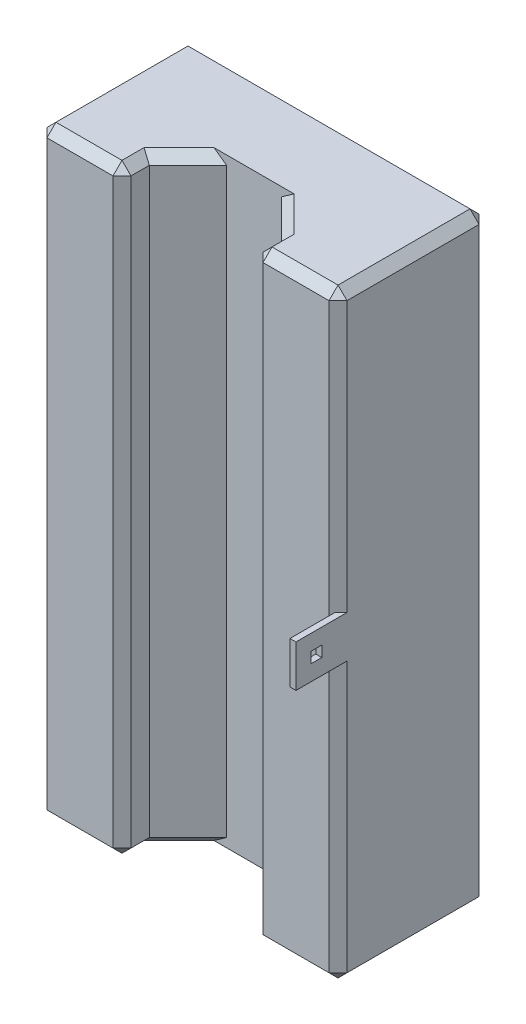
SolidWorks part; units mm, degrees
ref_plane "Front" through (0, 0, 0) normal (0, 0, 1) x (1, 0, 0)
ref_plane "Top" through (0, 0, 0) normal (0, 1, 0) x (1, 0, 0)
ref_plane "Right" through (0, 0, 0) normal (1, 0, 0) x (0, 0, -1)
sketch "Sketch1" plane through (0, 0, 0) normal (0, 0, 1) x (1, 0, 0)
  line L1 (0, 0) -> (50, 0)
  line L2 (0, 0) -> (0, 100)
  line L3 (0, 100) -> (50, 100)
  line L4 (50, 0) -> (50, 100)
  dimension "D1" = 50
  dimension "D2" = 100
extrude "Boss-Extrude1" add sketch "Sketch1" along normal blind 25
sketch "Sketch2" plane through (0, 0, 0) normal (0, -1, 0) x (1, 0, 0)
  line L0 (0, 25) -> (50, 25) construction
  line L1 (29.5563, 36) -> (20.4437, 36)
  line L2 (20.4437, 36) -> (14, 29.5563)
  line L3 (14, 29.5563) -> (14, 20.4437)
  line L4 (14, 20.4437) -> (20.4437, 14)
  line L5 (20.4437, 14) -> (29.5563, 14)
  line L6 (29.5563, 14) -> (36, 20.4437)
  line L7 (36, 20.4437) -> (36, 29.5563)
  line L8 (36, 29.5563) -> (29.5563, 36)
  circle A0 centre (25, 25) radius 11 construction
  dimension "D1" = 22
extrude "Cut-Extrude1" cut sketch "Sketch2" against normal through all
chamfer "Chamfer1" distance 1.5 angle 45 24 edges at (0, 50, 0) (0, 100, 12.5) (25, 100, 0) (32.7782, 100, 17.2218) (36, 100, 22.7218) (17.2218, 100, 17.2218) (14, 100, 22.7218) (7, 100, 25) (50, 100, 12.5) (43, 100, 25) (0, 50, 25) (14, 50, 25) (17.2218, 0, 17.2218) (14, 0, 22.7218) (7, 0, 25) (0, 0, 12.5) (25, 0, 0) (50, 50, 0) (50, 50, 25) (50, 0, 12.5) (32.7782, 0, 17.2218) (36, 0, 22.7218) (43, 0, 25) (36, 50, 25)
sketch "Sketch3" plane through (0, 0, 25) normal (0, 0, 1) x (1, 0, 0)
  line L0 (50, 98.5) -> (50, 1.5) construction
  line L1 (50, 53.5) -> (49, 53.5)
  line L2 (50, 53.5) -> (50, 46.5)
  line L3 (50, 46.5) -> (49, 46.5)
  line L4 (49, 53.5) -> (49, 46.5)
  point P6 (50, 50)
  dimension "D1" = 7
  dimension "D2" = 1
extrude "Boss-Extrude2" add sketch "Sketch3" along normal blind 7 and the other way blind 10
sketch "Sketch4" plane through (50, 0, 0) normal (1, 0, 0) x (0, 0, -1)
  line L0 (-29.5, 50) -> (-32, 50) construction
  line L1 (-29.5, 49.1) -> (-27.7, 49.1)
  line L2 (-29.5, 49.1) -> (-29.5, 50.9)
  line L3 (-29.5, 50.9) -> (-27.7, 50.9)
  line L4 (-27.7, 49.1) -> (-27.7, 50.9)
  line L5 (-32, 46.5) -> (-32, 53.5) construction
  dimension "D1" = 2.5
  dimension "D2" = 1.8
extrude "Cut-Extrude2" cut sketch "Sketch4" against normal blind 7
